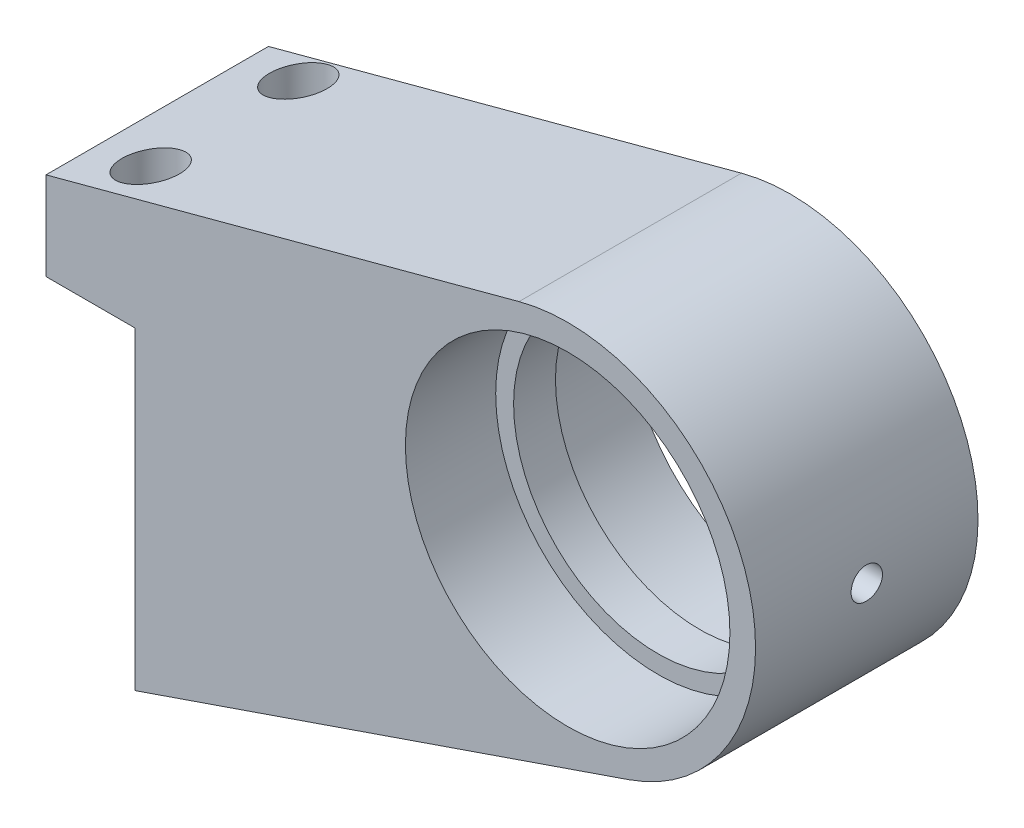
SolidWorks part; units mm, degrees
material "AISI Type 316L stainless steel"
ref_plane "Front Plane" through (0, 0, 0) normal (0, 0, 1) x (1, 0, 0)
ref_plane "Top Plane" through (0, 0, 0) normal (0, 1, 0) x (1, 0, 0)
ref_plane "Right Plane" through (0, 0, 0) normal (1, 0, 0) x (0, 0, -1)
sketch "Sketch1" plane through (0, 0, 0) normal (0, 0, 1) x (1, 0, 0)
  line L0 (-99.6659, 10.461) -> (-99.6659, -6.3775)
  line L1 (-99.6659, -6.3775) -> (-82.6659, -6.3775)
  line L2 (-82.6659, -6.3775) -> (-82.6659, -66.3775)
  line L3 (-99.6659, 10.461) -> (-9.2916, 34.6767)
  line L4 (-82.6659, -66.3775) -> (11.6701, -33.9502)
  line L6 (-82.6659, -6.3775) -> (-93.6659, -6.3775) construction
  line L7 (-82.6659, -6.3775) -> (-82.6659, -75.6257) construction
  line L8 (-82.6659, -75.6257) -> (-93.6659, -75.6257) construction
  line L9 (-93.6659, -6.3775) -> (-93.6659, -75.6257) construction
  arc A0 (-9.2916, 34.6767) -> (11.6701, -33.9502) centre (0, 0) cw
  circle A1 centre (0, 0) radius 31
  point P2 (-31, 0)
  point P16 (34.3341, 10.4872)
  dimension "D8" = 62
  dimension "D9" = 4.9
  dimension "D1" = 117
  dimension "D2" = 105
  dimension "D3" = 17
  dimension "D4" = 60
  dimension "D5" = 71.03
  dimension "D7" = 69.2482
extrude "Boss-Extrude1" add sketch "Sketch1" along normal mid plane 42.5
sketch "Sketch5" plane through (-82.6659, 0, 0) normal (-1, 0, 0) x (0, 0, 1)
  line L0 (-21.25, -66.3775) -> (8.75, -66.3775)
  line L1 (21.25, -66.3775) -> (-21.25, -66.3775) construction
  line L2 (-21.25, -66.3775) -> (-21.25, -36.3775)
  line L3 (-21.25, -6.3775) -> (-21.25, -66.3775) construction
  line L4 (-21.25, -36.3775) -> (8.75, -66.3775)
  dimension "D1" = 30
  dimension "D2" = 30
extrude "Cut-Extrude1" cut sketch "Sketch5" against normal blind 91
hole_wizard "Ø5.0mm Dowel Hole1" positions "Sketch7" profile "Sketch8" hole size "Ø5.0" standard "ANSI Metric"
sketch "Sketch7" plane through (-82.6659, 0, 0) normal (-1, 0, 0) x (0, 0, 1)
  line L0 (21.25, -6.3775) -> (21.25, -66.3775) construction
  line L1 (21.25, -66.3775) -> (8.75, -66.3775) construction
  point P0 (15.68, -60.6775)
  point P2 (15.68, -36.6775)
  point P4 (-98.6284, 36.7606)
  point P6 (0.68, -44.6775)
  point P17 (35.6, -82.2179)
  dimension "D1" = 5.57
  dimension "D2" = 24
  dimension "D3" = 5.7
  dimension "D4" = 16
  dimension "D5" = 15
sketch "Sketch8" plane through (-82.6659, -60.6775, 15.68) normal (0, 1, 0) x (0, 0, 1)
  line L0 (0, 0) -> (0, 9.5022)
  line L1 (0, 9.5022) -> (2.5, 8)
  line L2 (2.5, 8) -> (2.5, 0)
  line L5 (2.5, 0) -> (0, 0)
  line L10 (0, 9.5022) -> (-2.5, 8) construction
  line L11 (0, -6.35) -> (0, 107.95) construction
  dimension "Hole Dia." = 5
  dimension "Hole Depth" = 8
  dimension "Drill Angle" = 118
ref_plane "Plane1" through (0, 17.6225, 0) normal (0, -1, 0) x (-1, 0, 0)
hole_wizard "CBORE for M8 Hex Head Cap Screw2" positions "Sketch12" profile "Sketch13" counterbore size "M8" standard "ANSI Metric" end condition up to next
sketch "Sketch12" plane through (0, 17.6225, 0) normal (0, -1, 0) x (-1, 0, 0)
  line L0 (99.6659, -21.25) -> (99.6659, 21.25) construction
  line L1 (99.6659, 21.25) -> (82.6659, 21.25) construction
  point P0 (87.9659, 15.25)
  point P6 (87.9659, -12.95)
  dimension "D1" = 11.7
  dimension "D2" = 6
  dimension "D3" = 28.2
sketch "Sketch13" plane through (-87.9659, 17.6225, -15.25) normal (1, 0, 0) x (0, 0, 1)
  line L0 (0, 0) -> (0, 24)
  line L1 (0, 24) -> (3.25, 24)
  line L3 (3.25, 24) -> (3.25, 13)
  line L4 (3.25, 13) -> (5.5, 13)
  line L5 (5.5, 13) -> (5.5, 0)
  line L7 (5.5, 0) -> (0, 0)
  line L11 (0, -6.35) -> (0, 107.95) construction
  dimension "Thru Hole Dia." = 6.5
  dimension "Thru Hole Depth" = 24
  dimension "C'Bore Dia." = 11
  dimension "C'Bore Depth" = 13
ref_plane "Plane3" through (0, 0, 0) normal (0, 0, -1) x (-1, 0, 0)
sketch "Sketch18" plane through (0, 0, 0) normal (0, 0, -1) x (-1, 0, 0)
  circle A0 centre (0, 0) radius 27.58
  circle A1 centre (0, 0) radius 31
  dimension "D1" = 55.16
extrude "Boss-Extrude2" add sketch "Sketch18" along normal mid plane 8
sketch "Sketch21" plane through (0, 0, 0) normal (1, 0, 0) x (0, 0, -1)
  circle A0 centre (0, 0) radius 3
  dimension "D2" = 6
extrude "Cut-Extrude2" cut sketch "Sketch21" along normal through all
